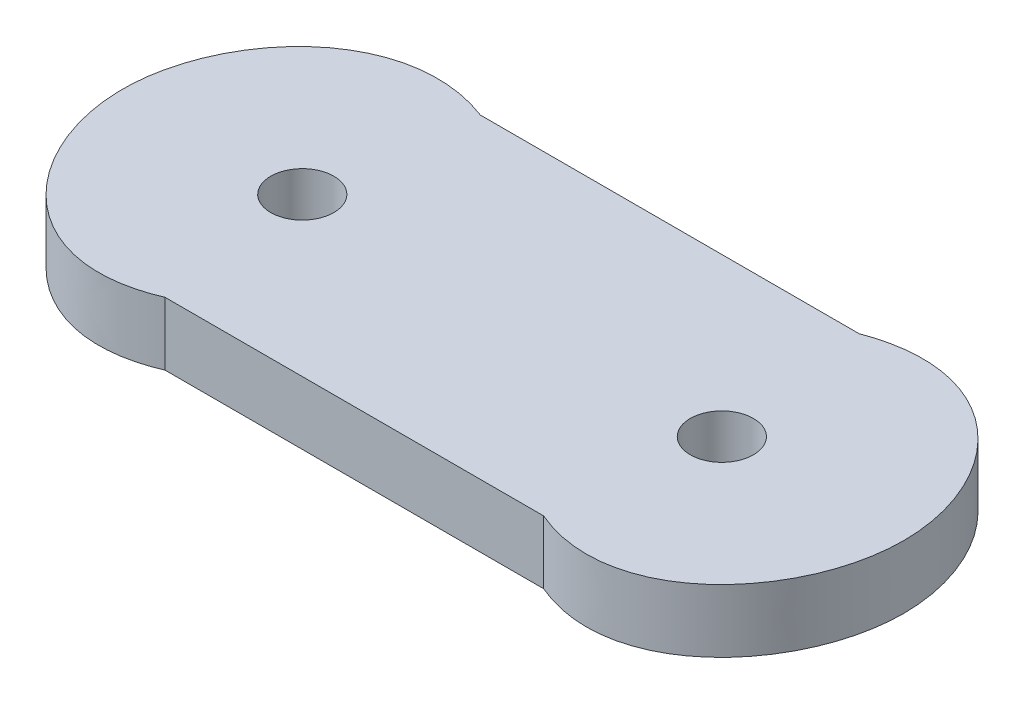
SolidWorks part; units mm, degrees
ref_plane "Plan de face" through (0, 0, 0) normal (0, 0, 1) x (1, 0, 0)
ref_plane "Plan de dessus" through (0, 0, 0) normal (0, 1, 0) x (1, 0, 0)
ref_plane "Plan de droite" through (0, 0, 0) normal (1, 0, 0) x (0, 0, -1)
sketch "Esquisse2" plane through (0, 0, 0) normal (0, 1, 0) x (1, 0, 0)
  line L0 (9, 7.5) -> (-9, 7.5)
  line L1 (0, -1.65) -> (0, 1.65) construction
  line L2 (-1.65, 0) -> (1.65, 0) construction
  line L3 (9, -7.5) -> (-9, -7.5)
  circle A0 centre (-9.9738, 0) radius 1.5
  circle A1 centre (-9.9738, 0) radius 8.6062 construction
  circle A2 centre (9.9738, 0) radius 1.5
  spline S0 degree 3 poles (-9, 7.5) (-14.3687, 9.5407) (-22.864, 0.063) (-14.2225, -9.744) (-9, -7.5) knots 0 0 0 0 0.498997 1 1 1 1
  spline S1 degree 3 poles (9, 7.5) (14.3687, 9.5407) (22.864, 0.063) (14.2225, -9.744) (9, -7.5) knots 0 0 0 0 0.498997 1 1 1 1
  point P11 (0, 7.5)
  point P13 (0, -7.5)
  dimension "D1" = 3
  dimension "D2" = 18
  dimension "D3" = 8.6062
  dimension "D4" = 15
  dimension "D5" = 6.9754
  dimension "D6" = 12.1666
  dimension "D8" = 6.1868
  dimension "D9" = 12.1666
extrude "Boss.-Extru.1" add sketch "Esquisse2" along normal blind 3
